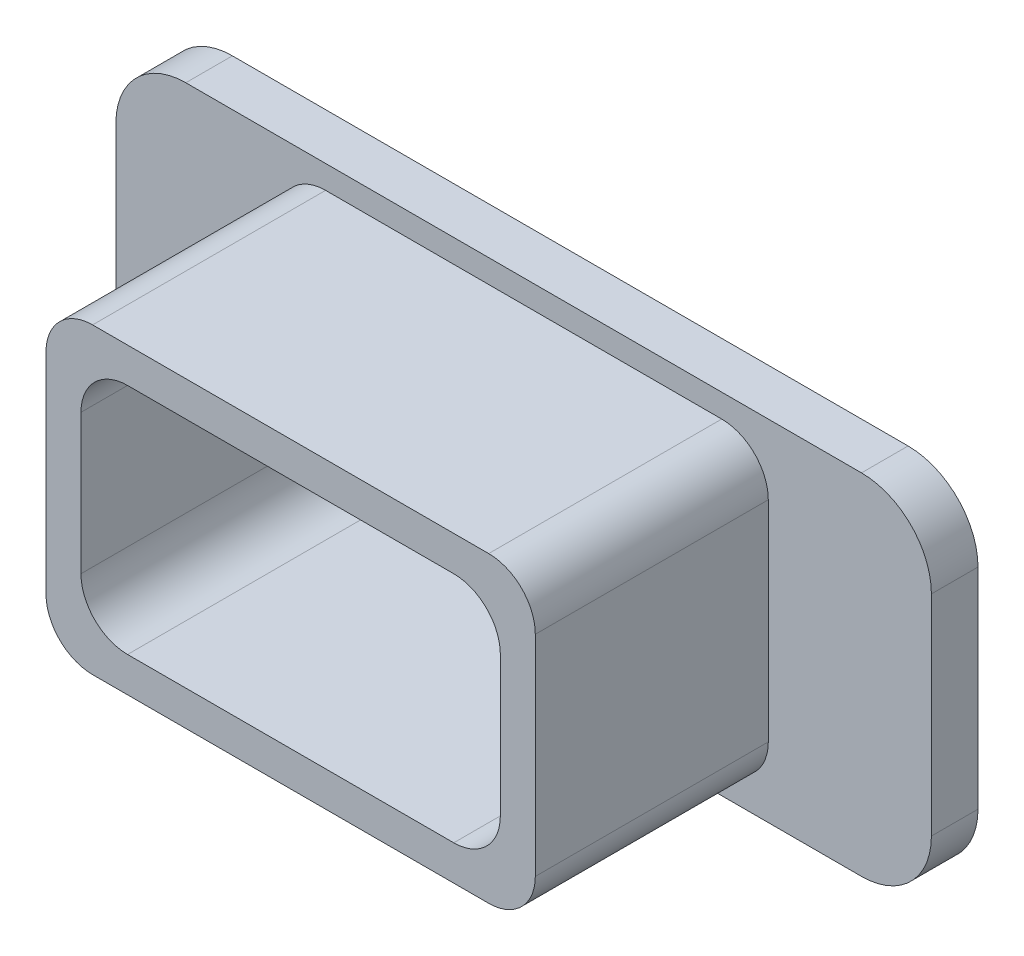
SolidWorks part; units mm, degrees
ref_plane "前视基准面" through (0, 0, 0) normal (0, 0, 1) x (1, 0, 0)
ref_plane "上视基准面" through (0, 0, 0) normal (0, 1, 0) x (1, 0, 0)
ref_plane "右视基准面" through (0, 0, 0) normal (1, 0, 0) x (0, 0, -1)
sketch "草图1" plane through (0, 0, 0) normal (0, 0, 1) x (1, 0, 0)
  line L1 (-9, 5) -> (9, 5)
  line L2 (-9, 5) -> (-9, -5)
  line L3 (-9, -5) -> (9, -5)
  line L4 (9, 5) -> (9, -5)
  line L5 (0, -5) -> (0, 5) construction
  line L6 (-9, 0) -> (9, 0) construction
  line L7 (-17.5, 7.5) -> (17.5, 7.5)
  line L8 (-17.5, 7.5) -> (-17.5, -7.5)
  line L9 (-17.5, -7.5) -> (17.5, -7.5)
  line L10 (17.5, 7.5) -> (17.5, -7.5)
  line L11 (0, -7.5) -> (0, 7.5) construction
  line L12 (-17.5, 0) -> (17.5, 0) construction
  point P0 (0, 0)
  point P4 (0, 0)
  dimension "D1" = 18
  dimension "D2" = 10
  dimension "D3" = 15
  dimension "D4" = 35
extrude "凸台-拉伸1" add sketch "草图1" along normal blind 2
sketch "草图2" plane through (0, 0, 2) normal (0, 0, 1) x (1, 0, 0)
  line L1 (-9, 5) -> (9, 5)
  line L2 (-9, 5) -> (-9, -5)
  line L3 (-9, -5) -> (9, -5)
  line L4 (9, 5) -> (9, -5)
  line L5 (0, -5) -> (0, 5) construction
  line L6 (-9, 0) -> (9, 0) construction
  line L7 (-10.5, 6.5) -> (10.5, 6.5)
  line L8 (-10.5, 6.5) -> (-10.5, -6.5)
  line L9 (-10.5, -6.5) -> (10.5, -6.5)
  line L10 (10.5, 6.5) -> (10.5, -6.5)
  line L11 (0, -6.5) -> (0, 6.5) construction
  line L12 (-10.5, 0) -> (10.5, 0) construction
  point P0 (0, 0)
  point P4 (0, 0)
  dimension "D1" = 1.5
  dimension "D2" = 1.5
extrude "凸台-拉伸2" add sketch "草图2" along normal blind 10
fillet "圆角1" radius 3 4 edges at (17.5, 7.5, 1) (17.5, -7.5, 1) (-17.5, -7.5, 1) (-17.5, 7.5, 1)
fillet "圆角2" radius 2 4 edges at (-9, 5, 6) (9, 5, 6) (-9, -5, 6) (9, -5, 6)
fillet "圆角3" radius 2 4 edges at (10.5, -6.5, 7) (10.5, 6.5, 7) (-10.5, 6.5, 7) (-10.5, -6.5, 7)
